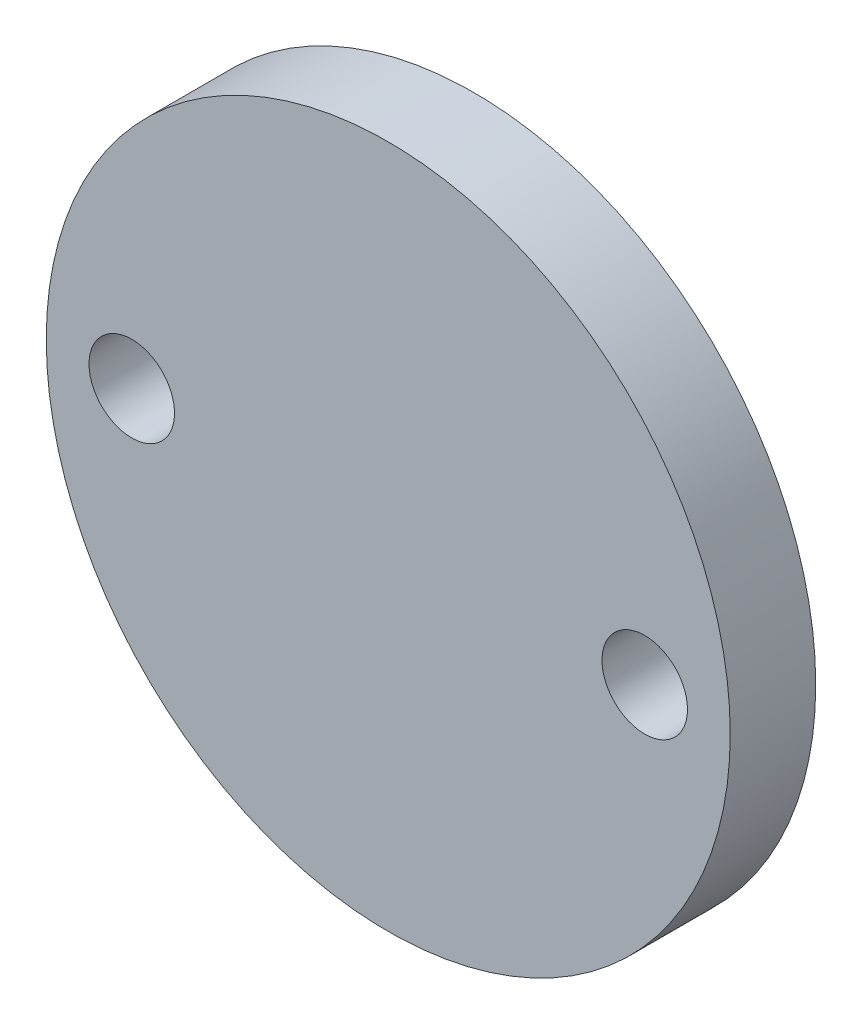
SolidWorks part; units mm, degrees
material "AISI 1020"
ref_plane "Front Plane" through (0, 0, 0) normal (0, 0, 1) x (1, 0, 0)
ref_plane "Top Plane" through (0, 0, 0) normal (0, 1, 0) x (1, 0, 0)
ref_plane "Right Plane" through (0, 0, 0) normal (1, 0, 0) x (0, 0, -1)
sketch "Sketch1" plane through (0, 0, 0) normal (0, 0, 1) x (1, 0, 0)
  line L0 (0, 40) -> (0, -40) construction
  line L1 (0, 0) -> (30, 0) construction
  circle A0 centre (0, 0) radius 40
  circle A2 centre (30, 0) radius 5
  circle A3 centre (-30, 0) radius 5
  dimension "D1" = 80
  dimension "D2" = 10
  dimension "D3" = 30
extrude "Boss-Extrude1" add sketch "Sketch1" along normal blind 10
